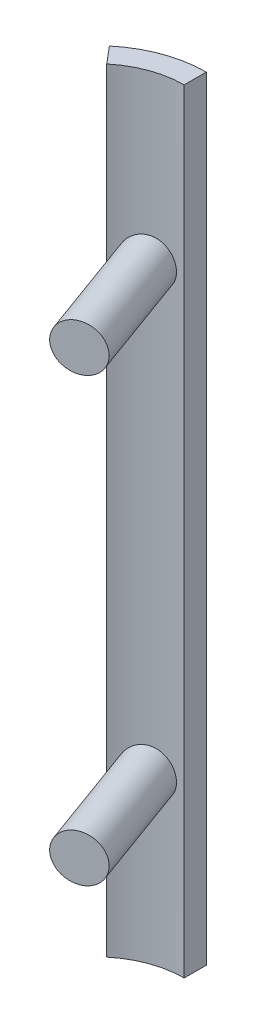
SolidWorks part; units mm, degrees
other "Markup1"
sketch "Sketch3" plane through (-5, 70, -6.9282) normal (-0.3723, 0.878, 0.3009) x (0.2286, -0.2274, 0.9466)
material "ABS"
ref_plane "Front Plane" through (0, 0, 0) normal (0, 0, 1) x (1, 0, 0)
ref_plane "Top Plane" through (0, 0, 0) normal (0, 1, 0) x (1, 0, 0)
ref_plane "Right Plane" through (0, 0, 0) normal (1, 0, 0) x (0, 0, -1)
sketch "Sketch1" plane through (0, 0, 0) normal (1, 0, 0) x (0, 0, -1)
  line L0 (0, 0) -> (0, 43155.5267) construction
  line L1 (0, 0) -> (10, 0)
  line L2 (10, 0) -> (10, 70)
  line L3 (10, 70) -> (0, 70)
  line L4 (0, 0) -> (0, 70)
  dimension "D1" = 70
  dimension "D2" = 10
revolve "Revolve1" add sketch "Sketch1" angle 40 about L0
sketch "Sketch2" plane through (0, 70, 0) normal (0, 1, 0) x (1, 0, 0)
  line L0 (-5.1423, 6.1284) -> (0, 0)
  line L1 (-6.4279, 7.6604) -> (0, 0) construction
  line L2 (0, 0) -> (0, 8)
  line L3 (0, 10) -> (0, 0) construction
  arc A0 (-5.1423, 6.1284) -> (0, 8) centre (0, 0) cw
  arc A1 (0, 10) -> (-6.4279, 7.6604) centre (0, 0) ccw construction
  dimension "D1" = 2
extrude "Cut-Extrude1" cut sketch "Sketch2" against normal through all
ref_plane "Plane1" through (-2.5712, 0, -7.0642) normal (0.342, 0, 0.9397) x (0.9397, 0, -0.342)
ref_plane "Plane2" through (0.8491, 0, 2.3327) normal (0.342, 0, 0.9397) x (0.9397, 0, -0.342)
sketch "Sketch4" plane through (0.8491, 0, 2.3327) normal (0.342, 0, 0.9397) x (0.9397, 0, -0.342)
  line L0 (-2.7362, 35) -> (49997.2638, 35) construction
  line L1 (-2.7362, 0) -> (-2.7362, 70) construction
  line L2 (3.4202, 0) -> (3.4202, 70) construction
  circle A0 centre (0, 55) radius 2.1
  circle A1 centre (0, 15) radius 2.1
  point P4 (-2.7362, 35)
  point P7 (3.4202, 35)
  point P12 (0, 0)
  dimension "D1" = 4.2
  dimension "D2" = 20
  dimension "D3" = 20
extrude "Boss-Extrude1" add sketch "Sketch4" against normal up to surface (10.2019 mm away)
